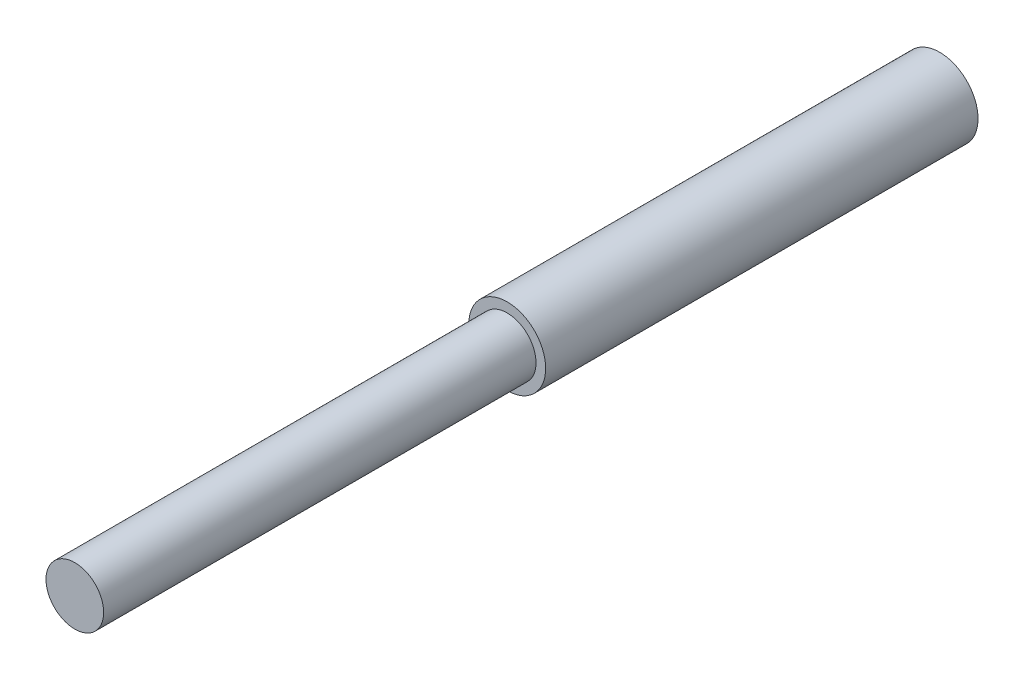
SolidWorks part; units mm, degrees
ref_plane "Front Plane" through (0, 0, 0) normal (0, 0, 1) x (1, 0, 0)
ref_plane "Top Plane" through (0, 0, 0) normal (0, 1, 0) x (1, 0, 0)
ref_plane "Right Plane" through (0, 0, 0) normal (1, 0, 0) x (0, 0, -1)
sketch "Sketch1" plane through (0, 0, 0) normal (0, 0, 1) x (1, 0, 0)
  circle A0 centre (0, 0) radius 4
  dimension "D1" = 8
extrude "Boss-Extrude1" add sketch "Sketch1" along normal blind 45
ref_plane "Plane1" through (0, 0, 45) normal (0, 0, 1) x (1, 0, 0)
sketch "Sketch2" plane through (0, 0, 45) normal (0, 0, 1) x (1, 0, 0)
  circle A0 centre (0, 0) radius 3
  dimension "D1" = 6
extrude "Boss-Extrude2" add sketch "Sketch2" along normal blind 45
